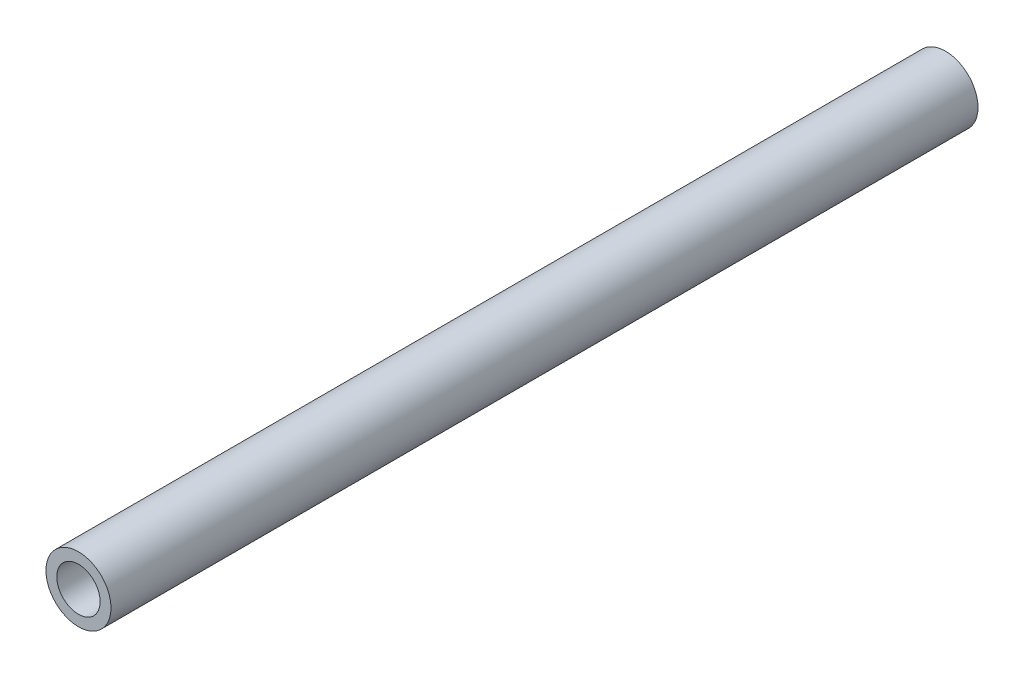
SolidWorks part; units mm, degrees
material "Alliage 1060"
ref_plane "Front" through (0, 0, 0) normal (0, 0, 1) x (1, 0, 0)
ref_plane "Top" through (0, 0, 0) normal (0, 1, 0) x (1, 0, 0)
ref_plane "Right" through (0, 0, 0) normal (1, 0, 0) x (0, 0, -1)
sketch "Esquisse1" plane through (0, 0, 0) normal (0, 0, 1) x (1, 0, 0)
  circle A0 centre (0, 0) radius 3
  dimension "D1" = 6
extrude "Extru.-Mince1" add sketch "Esquisse1" along normal blind 80 thin thin type one direction reverse wall 1
